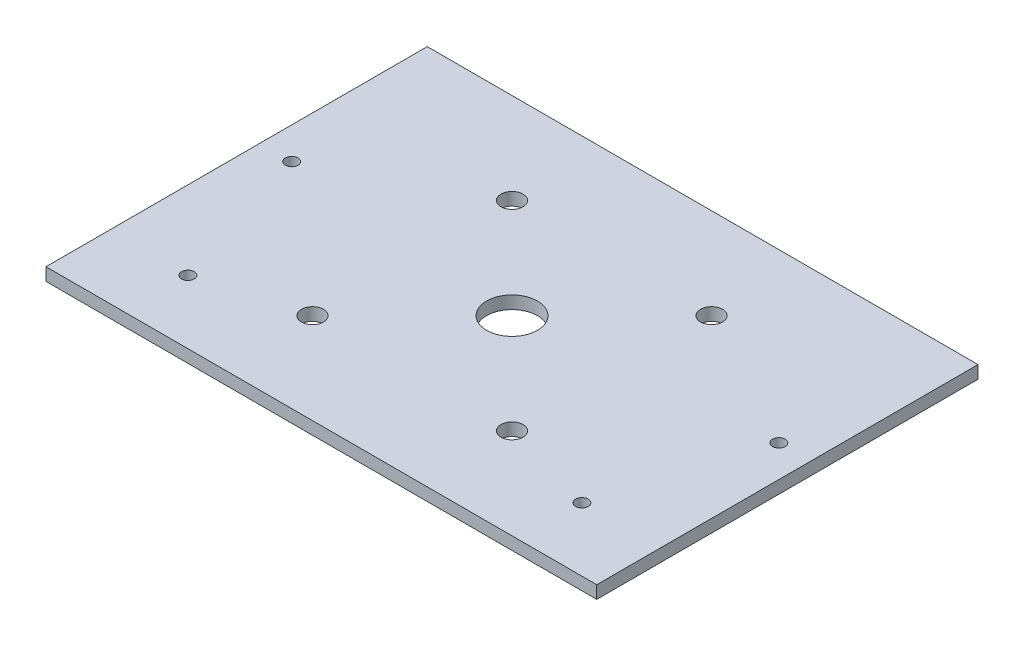
SolidWorks part; units mm, degrees
ref_plane "Front Plane" through (0, 0, 0) normal (0, 0, 1) x (1, 0, 0)
ref_plane "Top Plane" through (0, 0, 0) normal (0, 1, 0) x (1, 0, 0)
ref_plane "Right Plane" through (0, 0, 0) normal (1, 0, 0) x (0, 0, -1)
sketch "Sketch1" plane through (0, 0, 0) normal (0, 1, 0) x (1, 0, 0)
  line L1 (-65, 45) -> (65, 45)
  line L2 (-65, 45) -> (-65, -45)
  line L3 (-65, -45) -> (65, -45)
  line L4 (65, 45) -> (65, -45)
  line L5 (-65, 45) -> (65, -45) construction
  line L6 (-65, -45) -> (65, 45) construction
  point P0 (0, 0)
  dimension "D1" = 130
  dimension "D2" = 90
extrude "Boss-Extrude1" add sketch "Sketch1" along normal blind 3
sketch "Sketch2" plane through (0, 3, 0) normal (0, 1, 0) x (1, 0, 0)
  circle A0 centre (23.55, -23.55) radius 2.6
  circle A1 centre (-23.55, -23.55) radius 2.6
  circle A2 centre (-23.55, 23.55) radius 2.6
  circle A3 centre (23.55, 23.55) radius 2.6
  dimension "D1" = 5.2
extrude "Cut-Extrude1" cut sketch "Sketch2" against normal blind 10
sketch "Sketch3" plane through (0, 0, 0) normal (0, -1, 0) x (1, 0, 0)
  circle A0 centre (46.5, 30) radius 1.5
  circle A1 centre (-46.5, 30) radius 1.5
  circle A2 centre (-57.5, -5.5) radius 1.5
  circle A3 centre (57.5, -5.5) radius 1.5
  circle A4 centre (46.5, 30) radius 2.25 construction
  dimension "D1" = 3
  dimension "D2" = 0
extrude "Cut-Extrude2" cut sketch "Sketch3" against normal blind 10
sketch "Sketch4" plane through (0, 0, 0) normal (0, -1, 0) x (1, 0, 0)
  circle A0 centre (0, 0) radius 6
  dimension "D1" = 12
extrude "Cut-Extrude3" cut sketch "Sketch4" against normal blind 10
